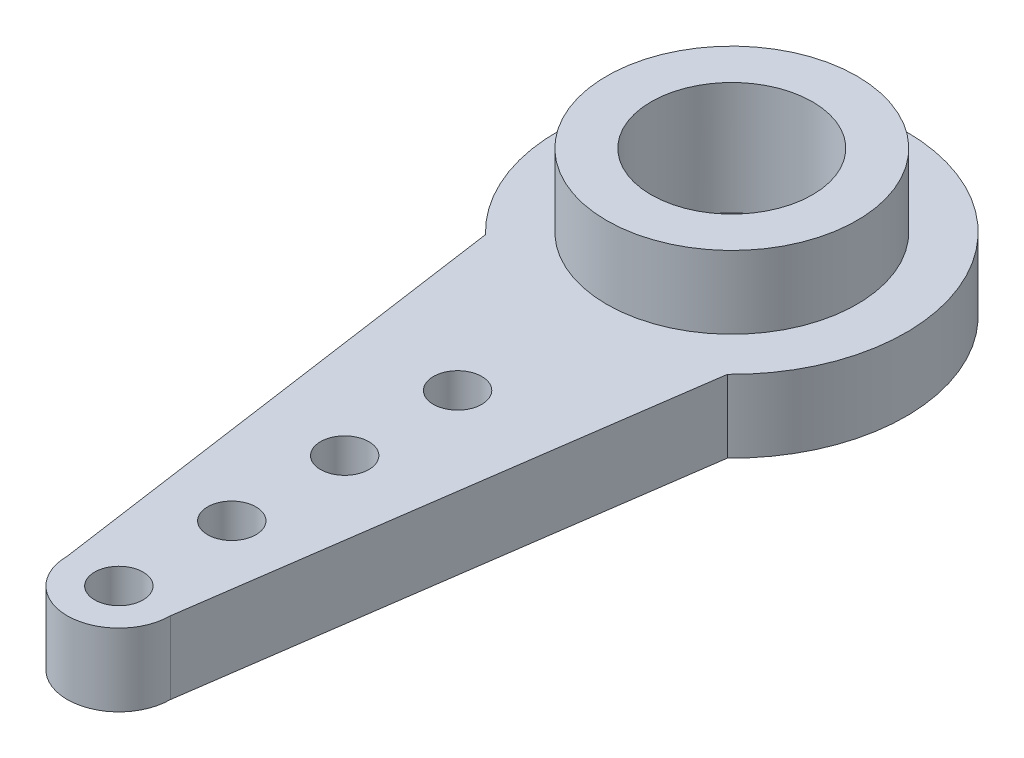
SolidWorks part; units mm, degrees
ref_plane "Front Plane" through (0, 0, 0) normal (0, 0, 1) x (1, 0, 0)
ref_plane "Top Plane" through (0, 0, 0) normal (0, 1, 0) x (1, 0, 0)
ref_plane "Right Plane" through (0, 0, 0) normal (1, 0, 0) x (0, 0, -1)
sketch "Sketch1" plane through (0, 0, 0) normal (0, 1, 0) x (1, 0, 0)
  line L0 (0, 0) -> (0, 2.5) construction
  line L1 (0, 0) -> (0, -19) construction
  line L2 (-1.6, 19) -> (-3.75, 3.8856)
  line L3 (1.6, 19) -> (3.75, 3.8856)
  line L4 (0, 0) -> (0, 19) construction
  line L5 (-3.75, 3.8856) -> (3.75, 3.8856) construction
  line L6 (1.6, -19) -> (3.75, -3.8856)
  line L7 (3.75, -3.8856) -> (-3.75, -3.8856) construction
  line L8 (-3.75, -3.8856) -> (-1.6, -19)
  circle A0 centre (0, 0) radius 2.5
  arc A1 (-3.75, 3.8856) -> (-3.75, -3.8856) centre (0, 0) ccw
  arc A2 (-1.6, -19) -> (1.6, -19) centre (0, -19) ccw
  arc A3 (1.6, 19) -> (-1.6, 19) centre (0, 19) ccw
  arc A4 (3.75, -3.8856) -> (3.75, 3.8856) centre (0, 0) ccw
  circle A5 centre (0, -19) radius 0.75
  circle A6 centre (0, 19) radius 0.75
  circle A7 centre (0, 15.5) radius 0.75
  circle A8 centre (0, 12) radius 0.75
  circle A9 centre (0, 8.5) radius 0.75
  circle A10 centre (0, -15.5) radius 0.75
  circle A11 centre (0, -12) radius 0.75
  circle A12 centre (0, -8.5) radius 0.75
  dimension "D1" = 5
  dimension "D2" = 10.8
  dimension "D4" = 3.2
  dimension "D6" = 1.5
  dimension "D7" = 3.5
  dimension "D8" = 3.5
  dimension "D9" = 3.5
  dimension "D11" = 3.5
  dimension "D12" = 3.5
  dimension "D13" = 3.5
  dimension "D3" = 19
  dimension "D5" = 7.5
extrude "Boss-Extrude1" add sketch "Sketch1" along normal blind 2.25
sketch "Sketch2" plane through (0, 2.25, 0) normal (0, 1, 0) x (1, 0, 0)
  circle A0 centre (0, 0) radius 2.5
  circle A1 centre (0, 0) radius 3.8795
extrude "Boss-Extrude2" add sketch "Sketch2" along normal blind 2.25
sketch "Sketch3" plane through (0, 0, 0) normal (0, -1, 0) x (1, 0, 0)
  circle A0 centre (0, 0) radius 2.0085
  circle A1 centre (0, 0) radius 2.5
extrude "Boss-Extrude3" add sketch "Sketch3" against normal blind 1
sketch "Sketch4" plane through (0, 0, 0) normal (0, -1, 0) x (1, 0, 0)
  circle A0 centre (0, 0) radius 3
  circle A1 centre (0, 0) radius 3.8
  dimension "D1" = 0.8
  dimension "D2" = 6
extrude "Cut-Extrude1" cut sketch "Sketch4" against normal blind 0.5
sketch "Sketch5" plane through (0, 0, 0) normal (0, -1, 0) x (1, 0, 0)
  line L4 (-3.75, -3.8856) -> (-1.6, -19)
  line L5 (1.6, -19) -> (3.75, -3.8856)
  line L6 (3.75, 3.8856) -> (1.6, 19)
  line L7 (-1.6, 19) -> (-3.75, 3.8856)
  line L8 (-3.75, -3.8856) -> (-1.6, -19)
  line L9 (1.6, -19) -> (3.75, -3.8856)
  arc A0 (-3.75, -3.8856) -> (3.75, -3.8856) centre (0, 0) ccw
  arc A4 (-3.75, 3.8856) -> (-3.75, -3.8856) centre (0, 0) ccw
  arc A5 (-1.6, -19) -> (1.6, -19) centre (0, -19) ccw
  arc A6 (3.75, -3.8856) -> (3.75, 3.8856) centre (0, 0) ccw
  arc A7 (1.6, 19) -> (-1.6, 19) centre (0, 19) ccw
  arc A9 (-1.6, -19) -> (1.6, -19) centre (0, -19) ccw
  dimension "D1" = 0
extrude "Cut-Extrude2" cut sketch "Sketch5" against normal through all
